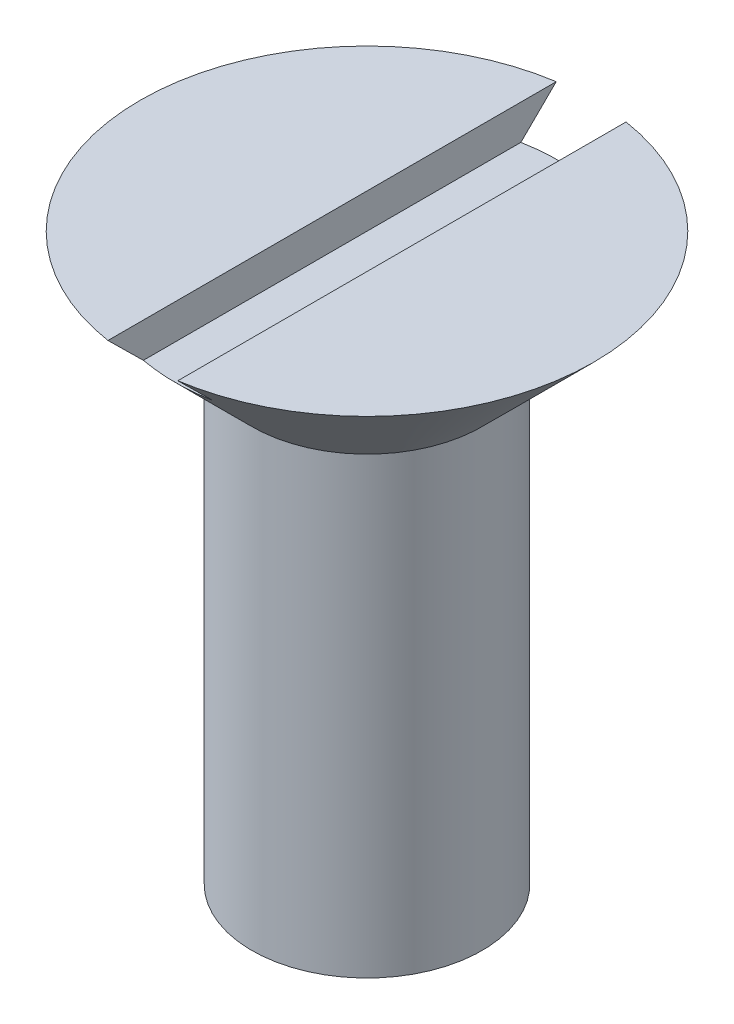
SolidWorks part; units mm, degrees
ref_plane "Front Plane" through (0, 0, 0) normal (0, 0, 1) x (1, 0, 0)
ref_plane "Top Plane" through (0, 0, 0) normal (0, 1, 0) x (1, 0, 0)
ref_plane "Right Plane" through (0, 0, 0) normal (1, 0, 0) x (0, 0, -1)
sketch "Sketch1" plane through (0, 0, 0) normal (0, 0, 1) x (1, 0, 0)
  line L11 (-6.5, 0) -> (-3.3, -3.2)
  line L12 (6.5, 0) -> (3.3, -3.2) construction
  line L13 (-3.3, -3.2) -> (-3.3, -16.2)
  line L14 (3.3, -3.2) -> (3.3, -16.2) construction
  line L15 (-3.3, -16.2) -> (0, -18.1053)
  line L16 (0, -18.1053) -> (3.3, -16.2) construction
  line L17 (-6.5, 0) -> (0, 0)
  line L18 (0, 0) -> (6.5, 0) construction
  line L19 (0, 0) -> (0, -18.1053)
  point P5 (0, 0)
  dimension "D1" = 13
  dimension "D4" = 6.6
  dimension "D5" = 13
  dimension "D6" = 120
revolve "Revolve1" add sketch "Sketch1" angle 360 about L19
sketch "Sketch2" plane through (0, 0, 0) normal (0, 0, 1) x (1, 0, 0)
  line L0 (-1, 0) -> (1, 0)
  line L1 (6.5, 0) -> (-6.5, 0) construction
  line L2 (1, 0) -> (1, -1)
  line L3 (-1, 0) -> (-1, -1)
  line L4 (-1, -1) -> (1, -1)
  point P5 (0, 0)
  dimension "D1" = 2
  dimension "D2" = 1
extrude "Cut-Extrude1" cut sketch "Sketch2" against normal through all and the other way through all
